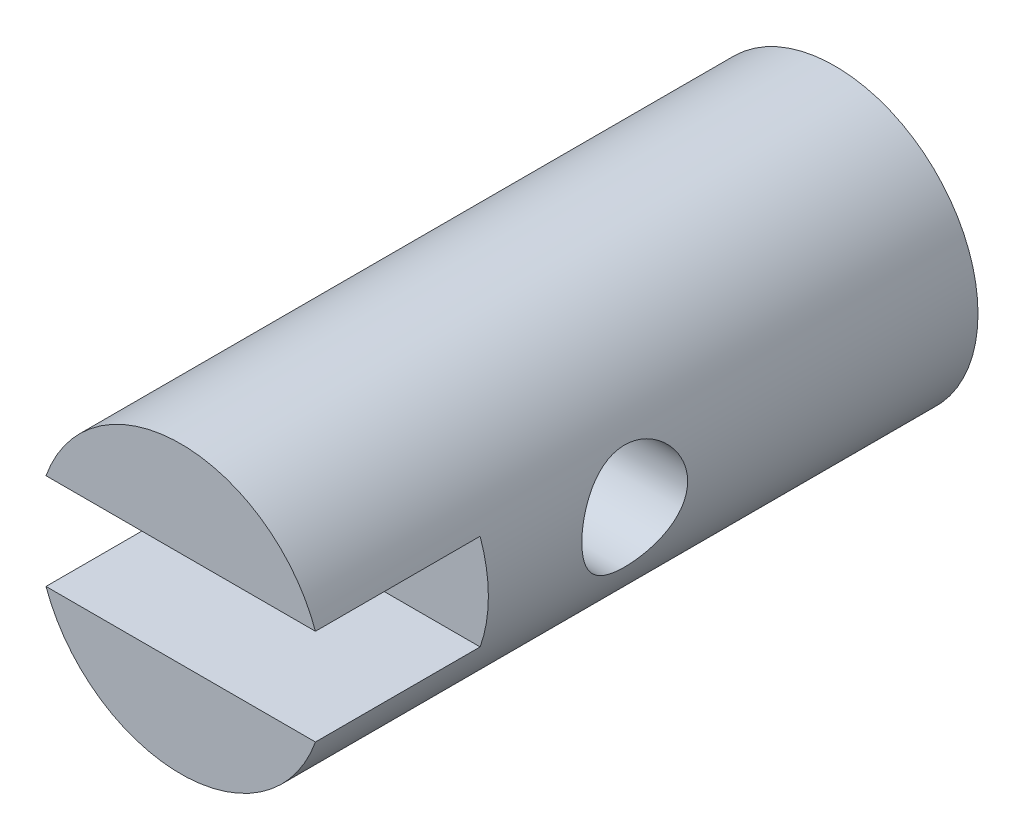
SolidWorks part; units mm, degrees
material "Pine"
ref_plane "Front Plane" through (0, 0, 0) normal (0, 0, 1) x (1, 0, 0)
ref_plane "Top Plane" through (0, 0, 0) normal (0, 1, 0) x (1, 0, 0)
ref_plane "Right Plane" through (0, 0, 0) normal (1, 0, 0) x (0, 0, -1)
sketch "Sketch1" plane through (0, 0, 0) normal (0, 0, 1) x (1, 0, 0)
  circle A0 centre (0, 0) radius 9.1313
  dimension "D1" = 18.2626
extrude "Boss-Extrude1" add sketch "Sketch1" along normal blind 41.783 contours A0
sketch "Sketch2" plane through (0, 0, 0) normal (1, 0, 0) x (0, 0, -1)
  line L0 (-41.783, 9.1313) -> (-41.783, -9.1313) construction
  circle A0 centre (-21.9202, 0) radius 3.3782
  point P4 (-21.9202, 0)
  dimension "D1" = 6.7564
  dimension "D2" = 19.8628
extrude "Cut-Extrude1" cut sketch "Sketch2" against normal through all both and the other way through all
sketch "Sketch3" plane through (0, 0, 0) normal (1, 0, 0) x (0, 0, -1)
  line L0 (-41.783, 3.0607) -> (-31.2674, 3.0607)
  line L1 (-41.783, 9.1313) -> (-41.783, -9.1313) construction
  line L2 (-31.2674, 3.0607) -> (-31.2674, -3.0607)
  line L3 (-31.2674, -3.0607) -> (-41.783, -3.0607)
  line L4 (-41.783, 3.0607) -> (-41.783, -3.0607)
  point P6 (-31.2674, 0)
  dimension "D1" = 6.1214
  dimension "D2" = 10.5156
extrude "Cut-Extrude3" cut sketch "Sketch3" against normal through all both and the other way through all
